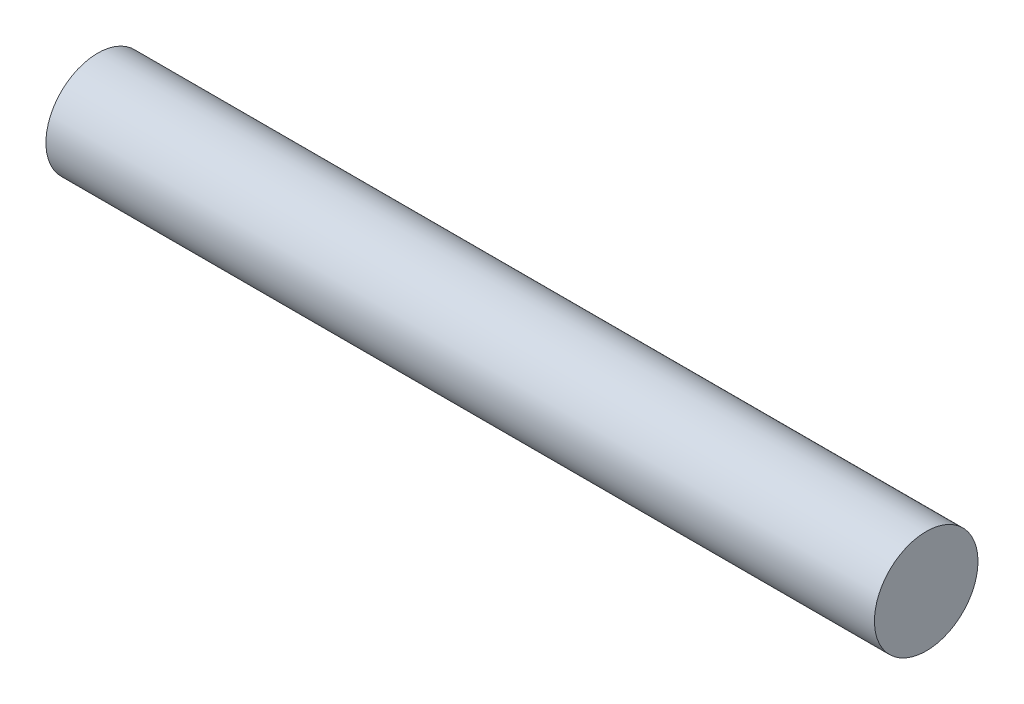
SolidWorks part; units mm, degrees
ref_plane "Front Plane" through (0, 0, 0) normal (0, 0, 1) x (1, 0, 0)
ref_plane "Top Plane" through (0, 0, 0) normal (0, 1, 0) x (1, 0, 0)
ref_plane "Right Plane" through (0, 0, 0) normal (1, 0, 0) x (0, 0, -1)
sketch "Sketch1" plane through (0, 0, 0) normal (1, 0, 0) x (0, 0, -1)
  circle A0 centre (0, 0) radius 1
  dimension "D1" = 2
extrude "Boss-Extrude1" add sketch "Sketch1" along normal blind 16
ref_plane "Plane1" through (8, 0, 0) normal (1, 0, 0) x (0, 0, -1)
